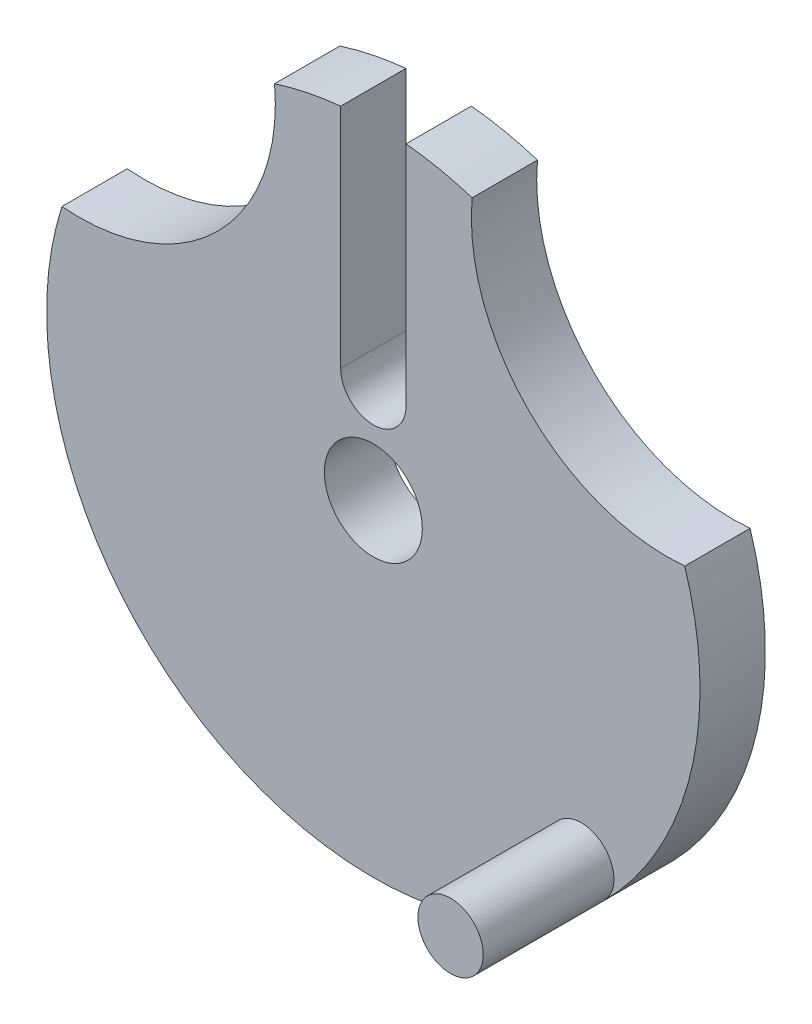
SolidWorks part; units mm, degrees
ref_plane "Front" through (0, 0, 0) normal (0, 0, 1) x (1, 0, 0)
ref_plane "Top" through (0, 0, 0) normal (0, 1, 0) x (1, 0, 0)
ref_plane "Right" through (0, 0, 0) normal (1, 0, 0) x (0, 0, -1)
sketch "Sketch1" plane through (0, 0, 0) normal (0, 0, 1) x (1, 0, 0)
  circle A0 centre (0, 0) radius 25
  dimension "D1" = 50
extrude "Boss-Extrude1" add sketch "Sketch1" along normal blind 5
sketch "Sketch2" plane through (0, 0, 5) normal (0, 0, 1) x (1, 0, 0)
  line L0 (-2.5, 7.5) -> (-2.5, 24.8747)
  line L1 (2.5, 7.5) -> (2.5, 24.8747)
  arc A0 (2.5, 24.8747) -> (-2.5, 24.8747) centre (0, 0) ccw
  circle A3 centre (0, 0) radius 25 construction
  arc A4 (-2.5, 7.5) -> (2.5, 7.5) centre (0, 7.5) ccw
  circle A5 centre (0, 0) radius 3.75
  dimension "D1" = 2.5
  dimension "D3" = 7.5
  dimension "D2" = 7.5
extrude "Cut-Extrude1" cut sketch "Sketch2" against normal through all
sketch "Sketch3" plane through (0, 0, 5) normal (0, 0, 1) x (1, 0, 0)
  line L0 (0, 0) -> (22.5, 22.5) construction
  line L1 (0, 0) -> (0, 24.8747) construction
  line L2 (0, -50) -> (0, 50) construction
  circle A0 centre (22.5, 22.5) radius 15
  circle A1 centre (-22.5, 22.5) radius 15
  dimension "D3" = 30
  dimension "D1" = 45
  dimension "D2" = 22.5
extrude "Cut-Extrude2" cut sketch "Sketch3" against normal through all
sketch "Sketch4" plane through (0, 0, 5) normal (0, 0, 1) x (1, 0, 0)
  line L0 (0, 0) -> (15.9099, -15.9099) construction
  line L1 (2.5, 7.5) -> (2.5, 24.8747) construction
  circle A0 centre (15.9099, -15.9099) radius 2.5
  arc A1 (-23.8298, 7.5591) -> (23.8298, 7.5591) centre (0, 0) ccw construction
  dimension "D1" = 5
  dimension "D2" = 135
extrude "Boss-Extrude2" add sketch "Sketch4" along normal blind 10
